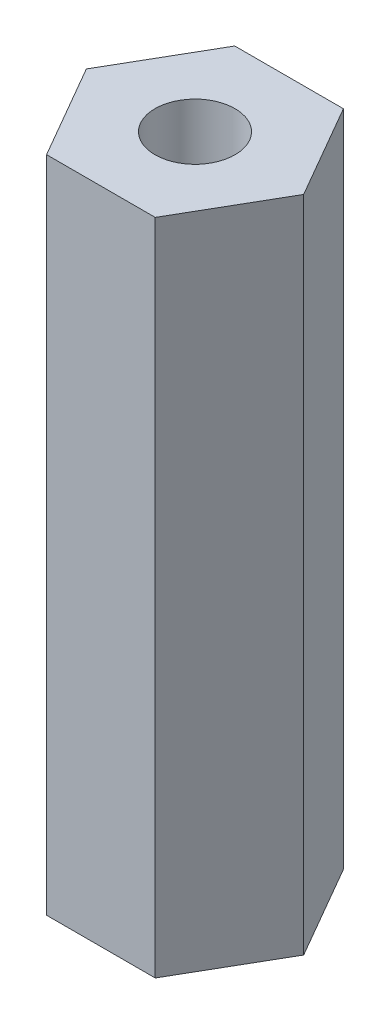
SolidWorks part; units mm, degrees
ref_plane "Front Plane" through (0, 0, 0) normal (0, 0, 1) x (1, 0, 0)
ref_plane "Top Plane" through (0, 0, 0) normal (0, 1, 0) x (1, 0, 0)
ref_plane "Right Plane" through (0, 0, 0) normal (1, 0, 0) x (0, 0, -1)
sketch "Sketch1" plane through (0, 0, 0) normal (0, 1, 0) x (1, 0, 0)
  line L1 (11.547, 0) -> (5.7735, 10)
  line L2 (5.7735, 10) -> (-5.7735, 10)
  line L3 (-5.7735, 10) -> (-11.547, 0)
  line L4 (-11.547, 0) -> (-5.7735, -10)
  line L5 (-5.7735, -10) -> (5.7735, -10)
  line L6 (5.7735, -10) -> (11.547, 0)
  circle A0 centre (0, 0) radius 10 construction
  circle A1 centre (0, 0) radius 4.25
  dimension "D1" = 8.5
  dimension "D2" = 20
extrude "Boss-Extrude1" add sketch "Sketch1" against normal blind 70
